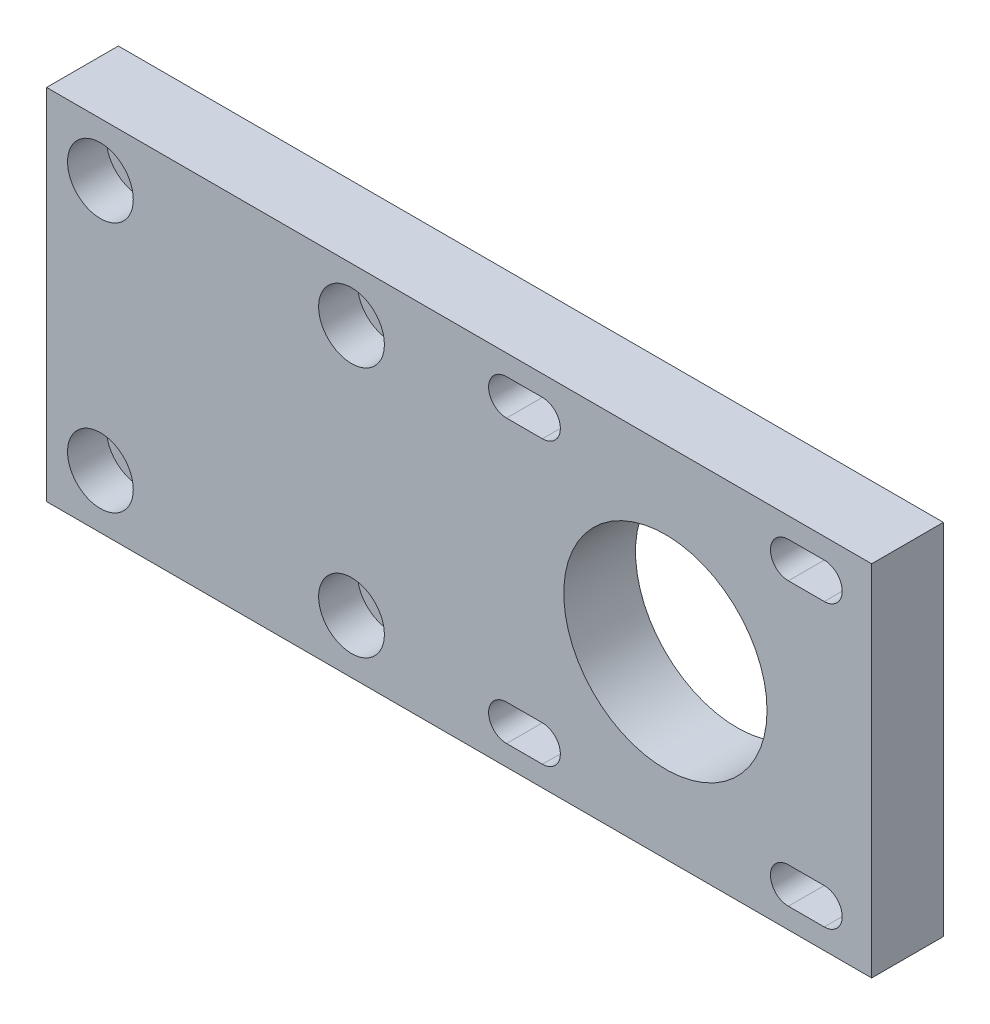
SolidWorks part; units mm, degrees
material "1.0037 (S235JR)"
ref_plane "Płaszczyzna przednia" through (0, 0, 0) normal (0, 0, 1) x (1, 0, 0)
ref_plane "Płaszczyzna górna" through (0, 0, 0) normal (0, 1, 0) x (1, 0, 0)
ref_plane "Płaszczyzna prawa" through (0, 0, 0) normal (1, 0, 0) x (0, 0, -1)
sketch "Szkic1" plane through (0, 0, 0) normal (0, 0, 1) x (1, 0, 0)
  line L0 (-70, 300) -> (-10, 300) construction
  line L1 (-70, 360) -> (68, 360)
  line L2 (-70, 360) -> (-70, 300)
  line L3 (-70, 300) -> (68, 300)
  line L4 (68, 360) -> (68, 300)
  circle A0 centre (33.5, 330) radius 17
  circle A1 centre (33.5, 330) radius 16 construction
  dimension "D1" = 34
  dimension "D2" = 138
extrude "Dodanie-wyciągnięcie1" add sketch "Szkic1" along normal blind 12
hole_wizard "Pogłębienie walcowe pod M5 Wkręt do części metalowych z łbem sześciokątnym1" positions "Szkic3" profile "Szkic2" counterbore size "M5" standard "Ansi Metric" end condition through all
sketch "Szkic3" plane through (0, 0, 12) normal (0, 0, 1) x (1, 0, 0)
  line L1 (-61, 351) -> (-19, 351)
  line L2 (-61, 351) -> (-61, 309)
  line L3 (-61, 309) -> (-19, 309)
  line L4 (-19, 351) -> (-19, 309)
  line L5 (68, 360) -> (-70, 360) construction
  line L6 (-70, 360) -> (-70, 300) construction
  point P0 (-61, 351)
  point P2 (-19, 351)
  point P4 (-61, 309)
  point P6 (-19, 309)
  dimension "D1" = 9
  dimension "D2" = 9
  dimension "D3" = 42
  dimension "D4" = 42
sketch "Szkic2" plane through (-61, 351, 12) normal (1, 0, 0) x (0, -1, 0)
  line L0 (0, 0) -> (0, 12)
  line L1 (0, 12) -> (2.75, 12)
  line L3 (2.75, 12) -> (2.75, 6.5)
  line L4 (2.75, 6.5) -> (5.5, 6.5)
  line L5 (5.5, 6.5) -> (5.5, 0)
  line L7 (5.5, 0) -> (0, 0)
  line L11 (0, -6.35) -> (0, 107.95) construction
  dimension "Średnica otworu na wylot" = 5.5
  dimension "Głębokość otworu na wylot" = 12
  dimension "Średnica pogłębienia walcowego" = 11
  dimension "Głębokość pogłębienia walcowego" = 6.5
sketch "Szkic5" plane through (0, 0, 0) normal (0, 0, -1) x (-1, 0, 0)
  line L0 (-12.93, 353.57) -> (-6.93, 353.57) construction
  line L1 (-12.93, 358.07) -> (-6.93, 358.07)
  line L2 (-12.93, 349.07) -> (-6.93, 349.07)
  line L3 (-60.07, 353.57) -> (-54.07, 353.57) construction
  line L4 (-60.07, 358.07) -> (-54.07, 358.07)
  line L5 (-60.07, 349.07) -> (-54.07, 349.07)
  arc A0 (-12.93, 358.07) -> (-12.93, 349.07) centre (-12.93, 353.57) ccw
  arc A1 (-6.93, 349.07) -> (-6.93, 358.07) centre (-6.93, 353.57) ccw
  circle A3 centre (-9.93, 353.57) radius 2.5 construction
  arc A4 (-60.07, 358.07) -> (-60.07, 349.07) centre (-60.07, 353.57) ccw
  arc A5 (-54.07, 349.07) -> (-54.07, 358.07) centre (-54.07, 353.57) ccw
  circle A6 centre (-57.07, 353.57) radius 2.5 construction
  point P2 (-9.93, 353.57)
  point P11 (-57.07, 353.57)
  dimension "D1" = 9
  dimension "D2" = 6
extrude "Wytnij-wyciągnięcie1" cut sketch "Szkic5" against normal blind 5
sketch "Szkic7" plane through (0, 0, 5) normal (0, 0, -1) x (-1, 0, 0)
  line L4 (-60.07, 350.57) -> (-54.07, 350.57)
  line L5 (-54.07, 356.57) -> (-60.07, 356.57)
  line L6 (-60.07, 350.57) -> (-54.07, 350.57)
  line L7 (-54.07, 356.57) -> (-60.07, 356.57)
  line L10 (-12.93, 350.57) -> (-6.93, 350.57)
  line L11 (-6.93, 356.57) -> (-12.93, 356.57)
  line L12 (-12.93, 350.57) -> (-6.93, 350.57)
  line L13 (-6.93, 356.57) -> (-12.93, 356.57)
  arc A4 (-60.07, 356.57) -> (-60.07, 350.57) centre (-60.07, 353.57) ccw
  arc A5 (-54.07, 350.57) -> (-54.07, 356.57) centre (-54.07, 353.57) ccw
  arc A6 (-60.07, 356.57) -> (-60.07, 350.57) centre (-60.07, 353.57) ccw
  arc A7 (-54.07, 350.57) -> (-54.07, 356.57) centre (-54.07, 353.57) ccw
  arc A10 (-12.93, 356.57) -> (-12.93, 350.57) centre (-12.93, 353.57) ccw
  arc A11 (-6.93, 350.57) -> (-6.93, 356.57) centre (-6.93, 353.57) ccw
  arc A12 (-12.93, 356.57) -> (-12.93, 350.57) centre (-12.93, 353.57) ccw
  arc A13 (-6.93, 350.57) -> (-6.93, 356.57) centre (-6.93, 353.57) ccw
  dimension "D1" = 1.5
  dimension "D2" = 1.5
extrude "Wytnij-wyciągnięcie2" cut sketch "Szkic7" against normal through all
ref_plane "Płaszczyzna1" through (0, 330, 0) normal (0, 1, 0) x (1, 0, 0)
mirror "Lustro1" about plane through (0, 330, 0) normal (0, 1, 0) of "Wytnij-wyciągnięcie2", "Wytnij-wyciągnięcie1"
equation "\"D2@Szkic3\"=\"D1@Szkic3\""
equation "\"D4@Szkic3\"=\"D3@Szkic3\""
